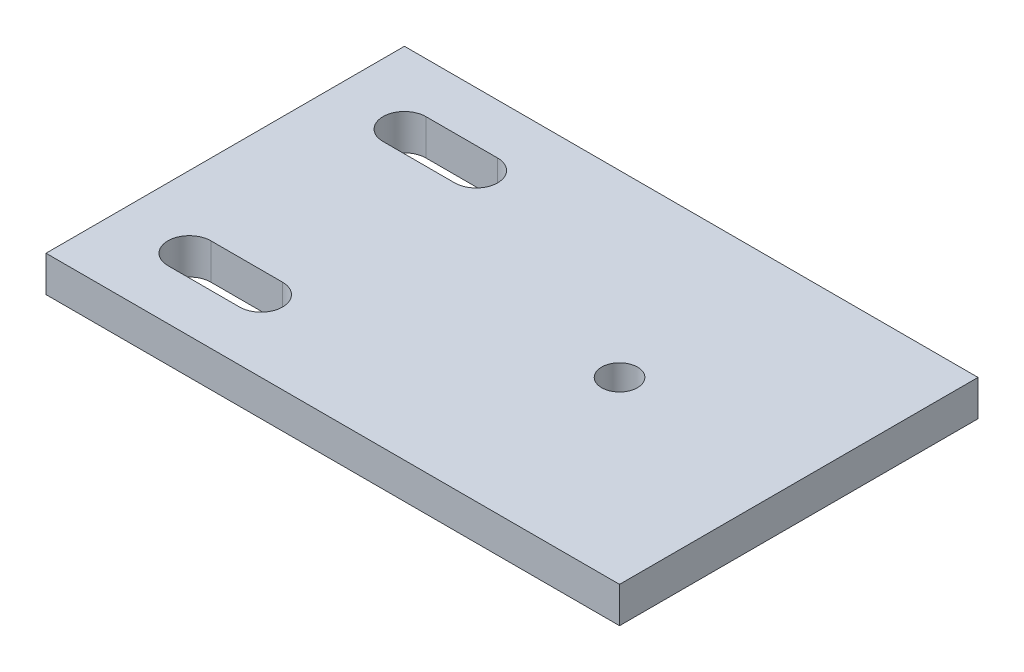
SolidWorks part; units mm, degrees
ref_plane "Front Plane" through (0, 0, 0) normal (0, 0, 1) x (1, 0, 0)
ref_plane "Top Plane" through (0, 0, 0) normal (0, 1, 0) x (1, 0, 0)
ref_plane "Right Plane" through (0, 0, 0) normal (1, 0, 0) x (0, 0, -1)
sketch "Sketch1" plane through (0, 0, 0) normal (0, 1, 0) x (1, 0, 0)
  line L0 (10, 40) -> (20, 40) construction
  line L1 (0, 0) -> (80, 0)
  line L2 (0, 0) -> (0, 50)
  line L3 (0, 50) -> (80, 50)
  line L4 (80, 0) -> (80, 50)
  line L5 (10, 43) -> (20, 43)
  line L6 (10, 37) -> (20, 37)
  line L7 (10, 10) -> (20, 10) construction
  line L8 (10, 13) -> (20, 13)
  line L9 (10, 7) -> (20, 7)
  arc A0 (10, 43) -> (10, 37) centre (10, 40) ccw
  arc A1 (20, 37) -> (20, 43) centre (20, 40) ccw
  arc A2 (10, 13) -> (10, 7) centre (10, 10) ccw
  arc A3 (20, 7) -> (20, 13) centre (20, 10) ccw
  circle A4 centre (55, 25) radius 2.5
  point P7 (15, 40)
  point P14 (15, 10)
  dimension "D4" = 3
  dimension "D7" = 3
  dimension "D10" = 5
  dimension "D1" = 50
  dimension "D2" = 80
  dimension "D3" = 15
  dimension "D5" = 10
  dimension "D6" = 10
  dimension "D8" = 10
  dimension "D9" = 25
extrude "Boss-Extrude1" add sketch "Sketch1" along normal blind 5
